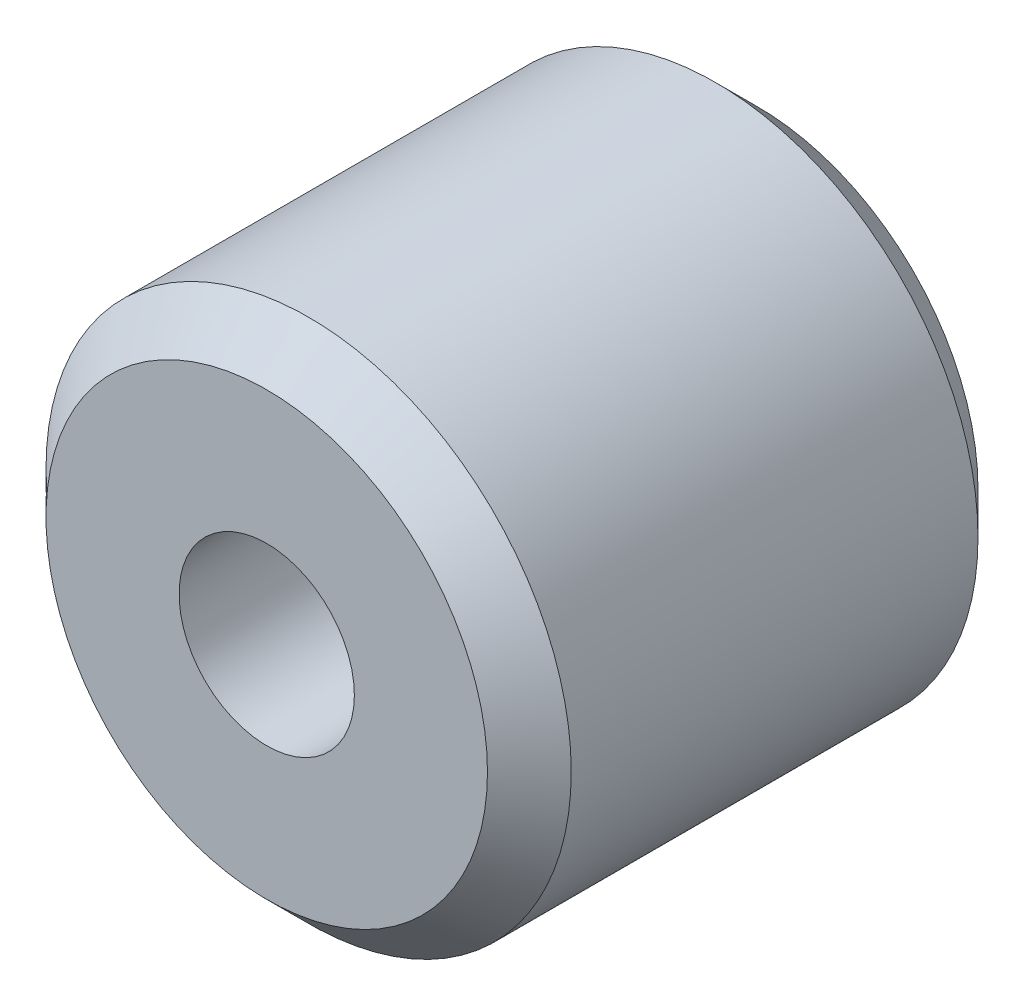
SolidWorks part; units mm, degrees
ref_plane "Front Plane" through (0, 0, 0) normal (0, 0, 1) x (1, 0, 0)
ref_plane "Top Plane" through (0, 0, 0) normal (0, 1, 0) x (1, 0, 0)
ref_plane "Right Plane" through (0, 0, 0) normal (1, 0, 0) x (0, 0, -1)
sketch "Sketch1" plane through (0, 0, 0) normal (0, 0, 1) x (1, 0, 0)
  circle A0 centre (0, 0) radius 4.765
  circle A1 centre (0, 0) radius 1.59
  dimension "D1" = 3.18
  dimension "D2" = 9.53
extrude "Boss-Extrude1" add sketch "Sketch1" along normal mid plane 8.9
chamfer "Chamfer1" distance 0.76 angle 45 2 edges at (4.765, 0, -4.45) (4.765, 0, 4.45)
